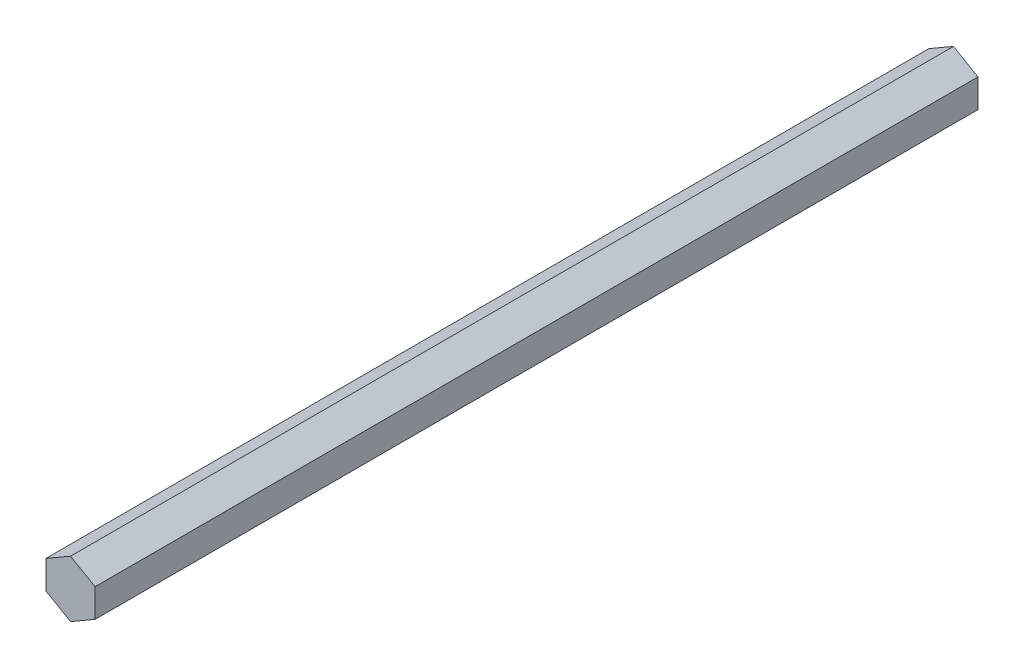
SolidWorks part; units mm, degrees
ref_plane "Front Plane" through (0, 0, 0) normal (0, 0, 1) x (1, 0, 0)
ref_plane "Top Plane" through (0, 0, 0) normal (0, 1, 0) x (1, 0, 0)
ref_plane "Right Plane" through (0, 0, 0) normal (1, 0, 0) x (0, 0, -1)
sketch "Sketch1" plane through (0, 0, 0) normal (0, 0, 1) x (1, 0, 0)
  line L0 (0, 0) -> (0, 7.3323)
  line L1 (0, 7.3323) -> (-6.35, 3.6662)
  line L2 (-6.35, 3.6662) -> (-6.35, -3.6662)
  line L3 (-6.35, -3.6662) -> (0, -7.3323)
  line L4 (0, -7.3323) -> (6.35, -3.6662)
  line L5 (6.35, -3.6662) -> (6.35, 3.6662)
  line L6 (6.35, 3.6662) -> (0, 7.3323)
  circle A0 centre (0, 0) radius 6.35 construction
  dimension "D1" = 12.7
extrude "Boss-Extrude1" add sketch "Sketch1" along normal blind 228.6
